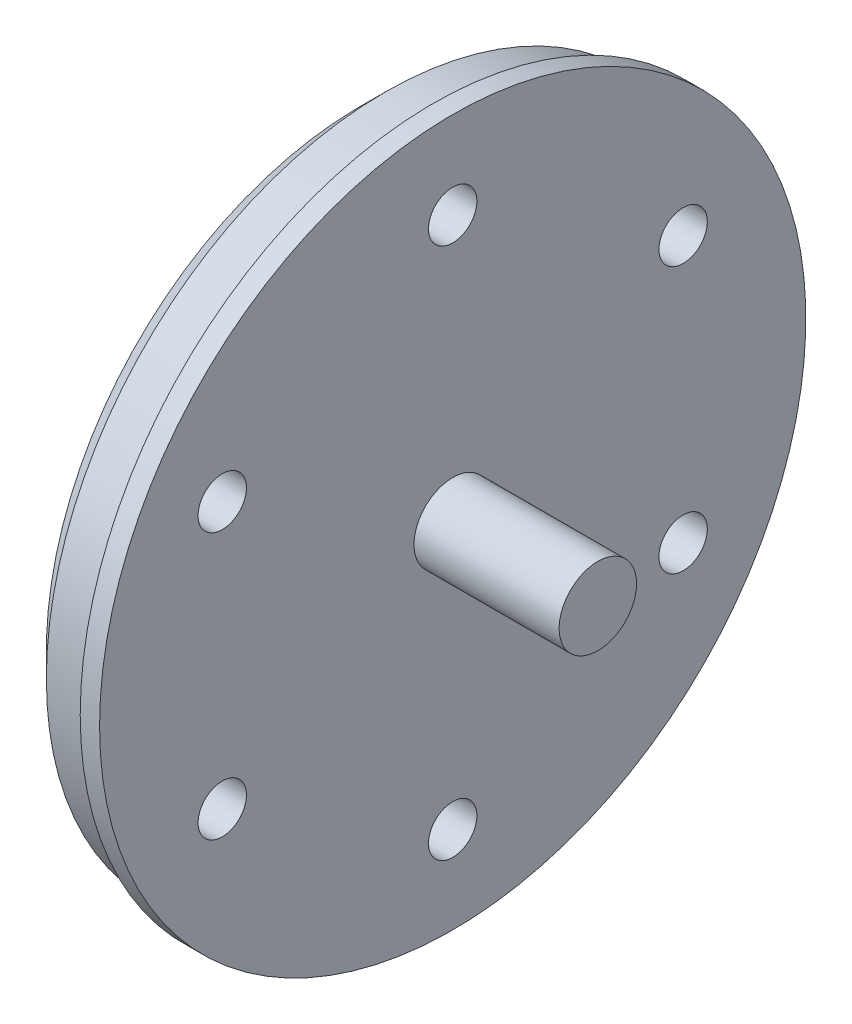
SolidWorks part; units mm, degrees
material "6061-T6 (SS)"
ref_plane "Front Plane" through (0, 0, 0) normal (0, 0, 1) x (1, 0, 0)
ref_plane "Top Plane" through (0, 0, 0) normal (0, 1, 0) x (1, 0, 0)
ref_plane "Right Plane" through (0, 0, 0) normal (1, 0, 0) x (0, 0, -1)
sketch "Sketch1" plane through (0, 0, 0) normal (1, 0, 0) x (0, 0, -1)
  circle A0 centre (0, 0) radius 7.5 construction
  circle A1 centre (0, 0) radius 35
  dimension "D1" = 15
  dimension "D2" = 70
extrude "Boss-Extrude1" add sketch "Sketch1" along normal blind 9.5
sketch "Sketch2" plane through (9.5, 0, 0) normal (1, 0, 0) x (0, 0, -1)
  circle A1 centre (0, 0) radius 4
  dimension "D1" = 8
extrude "Boss-Extrude2" add sketch "Sketch2" along normal blind 15
sketch "Sketch3" plane through (9.5, 0, 0) normal (-1, 0, 0) x (0, 0, 1)
  circle A4 centre (0, 0) radius 36.5
  dimension "D1" = 73
extrude "Boss-Extrude3" add sketch "Sketch3" along normal blind 2
sketch "Sketch4" plane through (0, 0, 0) normal (-1, 0, 0) x (0, 0, 1)
  circle A0 centre (0, 0) radius 27.5 construction
  circle A1 centre (0, 27.5) radius 2.5
  circle A2 centre (23.8157, 13.75) radius 2.5
  circle A3 centre (23.8157, -13.75) radius 2.5
  circle A4 centre (0, -27.5) radius 2.5
  circle A5 centre (-23.8157, -13.75) radius 2.5
  circle A6 centre (-23.8157, 13.75) radius 2.5
  point P6 (0, 0)
  point P17 (0, 0)
  dimension "D1" = 55
  dimension "D2" = 5
  dimension "D3" = 6
extrude "Cut-Extrude1" cut sketch "Sketch4" against normal offset from surface (17.5 mm away) 10 up to face at (7.5, 0, 35)
sketch "Sketch5" plane through (0, 0, 0) normal (-1, 0, 0) x (0, 0, 1)
  circle A2 centre (0, 0) radius 20
  dimension "D1" = 40
extrude "Cut-Extrude2" cut sketch "Sketch5" against normal up to surface (7.5 mm away) up to face at (7.5, 0, 35)
chamfer "Chamfer1" distance 2.5 angle 45 3 edges at (7.5, 0, 20) (0, 0, -35) (0, 0, 20)
